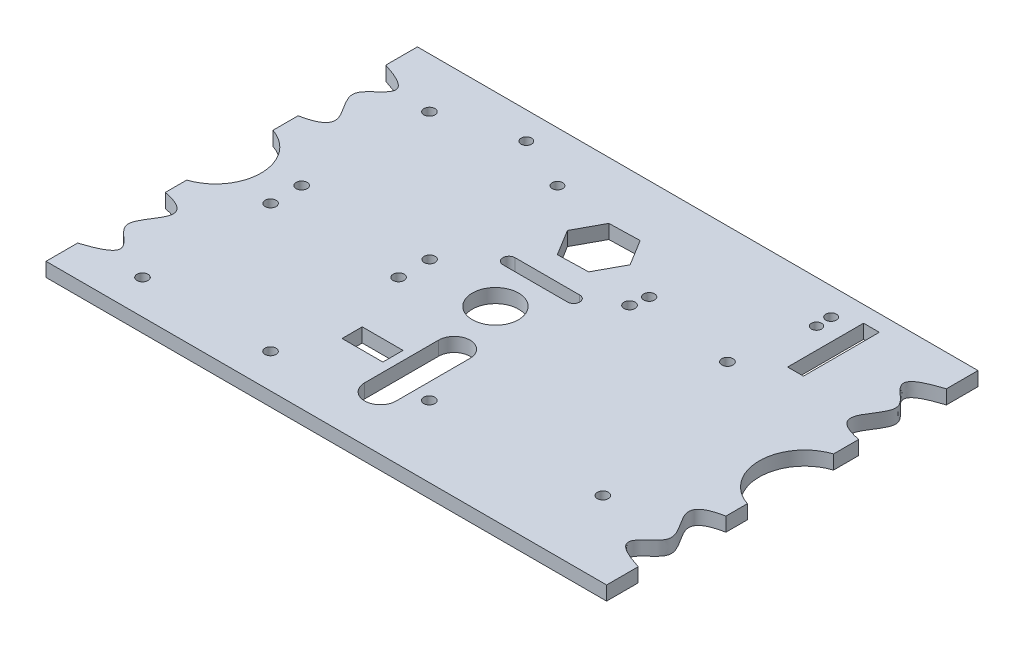
SolidWorks part; units mm, degrees
ref_plane "Front Plane" through (0, 0, 0) normal (0, 0, 1) x (1, 0, 0)
ref_plane "Top Plane" through (0, 0, 0) normal (0, 1, 0) x (1, 0, 0)
ref_plane "Right Plane" through (0, 0, 0) normal (1, 0, 0) x (0, 0, -1)
sketch "Sketch1" plane through (0, 0, 0) normal (0, 1, 0) x (1, 0, 0)
  line L0 (0, 0) -> (0, 70.7426) construction
  line L1 (80, 53) -> (-80, 53)
  line L2 (80, 53) -> (80, -53)
  line L3 (80, -53) -> (-80, -53)
  line L4 (-80, 53) -> (-80, -53)
  line L5 (0, 0) -> (109.5414, 0) construction
  line L6 (-80, -16.4693) -> (-80, -48.3678)
  line L10 (0, -37.5523) -> (0, -16.4693) construction
  line L11 (-4.4998, -37.5523) -> (-4.4998, -16.4693)
  line L12 (4.4998, -37.5523) -> (4.4998, -16.4693)
  line L13 (4.4998, 13.0904) -> (-13.9507, 13.0904) construction
  line L14 (-7.025, -24.0711) -> (-18.669, -24.0711)
  line L15 (-7.025, -24.0711) -> (-7.025, -29.8364)
  line L16 (-7.025, -29.8364) -> (-18.669, -29.8364)
  line L17 (-18.669, -24.0711) -> (-18.669, -29.8364)
  line L18 (4.4998, 11.3473) -> (-13.9507, 11.3473)
  line L19 (4.4998, 14.8334) -> (-13.9507, 14.8334)
  line L21 (-8.6559, 21.5986) -> (0.0582, 21.8306)
  line L22 (0.0582, 21.8306) -> (4.2143, 29.4932)
  line L23 (4.2143, 29.4932) -> (-0.3436, 36.9238)
  line L24 (-0.3436, 36.9238) -> (-9.0577, 36.6918)
  line L25 (-9.0577, 36.6918) -> (-13.2139, 29.0292)
  line L26 (-13.2139, 29.0292) -> (-8.6559, 21.5986)
  line L27 (51.9664, 48.3678) -> (56.4728, 48.3678)
  line L28 (51.9664, 48.3678) -> (51.9664, 26.6955)
  line L29 (51.9664, 26.6955) -> (56.4728, 26.6955)
  line L30 (56.4728, 48.3678) -> (56.4728, 26.6955)
  arc A0 (-80, -12.8265) -> (-80, 11.7732) centre (-84.0546, -0.5266) ccw
  circle A1 centre (-62.2504, 38.6873) radius 1.5728
  circle A2 centre (9.0805, -32.68) radius 1.5875
  circle A3 centre (57.3405, -31.41) radius 1.5875
  circle A4 centre (14.1605, 19.39) radius 1.5875
  circle A5 centre (42.1005, 19.39) radius 1.5875
  circle A6 centre (-25.7146, -6.6473) radius 1.5727
  circle A7 centre (-62.2504, -6.6473) radius 1.5727
  circle A8 centre (-62.2504, -43.2084) radius 1.5727
  circle A9 centre (-25.7146, -43.2084) radius 1.5727
  arc A10 (-4.4998, -37.5523) -> (4.4998, -37.5523) centre (0, -37.5523) ccw
  arc A11 (4.4998, -16.4693) -> (-4.4998, -16.4693) centre (0, -16.4693) ccw
  arc A12 (4.4998, 11.3473) -> (4.4998, 14.8334) centre (4.4998, 13.0904) ccw
  arc A13 (-13.9507, 14.8334) -> (-13.9507, 11.3473) centre (-13.9507, 13.0904) ccw
  circle A14 centre (-4.4998, 29.2612) radius 7.5493 construction
  circle A15 centre (-4.7255, 0) radius 6.5984
  circle A16 centre (-25.7146, 38.6873) radius 1.5
  circle A17 centre (-25.7146, 2.2101) radius 1.56
  circle A18 centre (-62.2504, 2.2101) radius 1.5735
  arc A19 (80, -12.8265) -> (80, 11.7732) centre (84.0546, -0.5266) cw
  circle A20 centre (14.8949, 24.261) radius 1.5376
  circle A21 centre (45.9834, 40.9244) radius 1.4553
  spline S0 degree 3 poles (-80, -43.9717) (-65.3857, -39.4048) (-89.0775, -33.6276) (-66.5269, -21.603) (-80, -18.9482) knots 0 0 0 0 0.464081 1 1 1 1
  spline S1 degree 3 poles (-80, 43.9717) (-65.3857, 39.4048) (-89.0775, 33.6276) (-66.5269, 21.603) (-80, 18.9482) knots 0 0 0 0 0.464081 1 1 1 1
  spline S2 degree 3 poles (80, 43.9717) (65.3857, 39.4048) (89.0775, 33.6276) (66.5269, 21.603) (80, 18.9482) knots 0 0 0 0 0.464081 1 1 1 1
  spline S3 degree 3 poles (80, -43.9717) (65.3857, -39.4048) (89.0775, -33.6276) (66.5269, -21.603) (80, -18.9482) knots 0 0 0 0 0.464081 1 1 1 1
  spline S6 degree 3 poles (47.3426, 45.238) (47.3426, 48.238) (44.3426, 48.238) (44.3426, 45.238) (44.3426, 42.238) (47.3426, 42.238) (47.3426, 45.238) (47.3426, 48.238) (44.3426, 48.238) knots -0.5 0 0 0 0.5 0.5 0.5 1 1 1 1.5 1.5 1.5 weights 1 0.333333 0.333333 1 0.333333 0.333333 1 0.333333 0.333333 only from (47.3426, 45.238) to (47.3426, 45.238) construction
  spline S7 degree 3 poles (-39.6524, 45.238) (-39.6524, 48.238) (-42.6524, 48.238) (-42.6524, 45.238) (-42.6524, 42.238) (-39.6524, 42.238) (-39.6524, 45.238) (-39.6524, 48.238) (-42.6524, 48.238) knots -0.5 0 0 0 0.5 0.5 0.5 1 1 1 1.5 1.5 1.5 weights 1 0.333333 0.333333 1 0.333333 0.333333 1 0.333333 0.333333 only from (-39.6524, 45.238) to (-39.6524, 45.238) construction
  spline S8 degree 3 poles (47.3426, 45.238) (47.3426, 48.238) (44.3426, 48.238) (44.3426, 45.238) (44.3426, 42.238) (47.3426, 42.238) (47.3426, 45.238) (47.3426, 48.238) (44.3426, 48.238) knots -0.5 0 0 0 0.5 0.5 0.5 1 1 1 1.5 1.5 1.5 weights 1 0.333333 0.333333 1 0.333333 0.333333 1 0.333333 0.333333 only from (47.3426, 45.238) to (47.3426, 45.238)
  spline S9 degree 3 poles (-39.6524, 45.238) (-39.6524, 48.238) (-42.6524, 48.238) (-42.6524, 45.238) (-42.6524, 42.238) (-39.6524, 42.238) (-39.6524, 45.238) (-39.6524, 48.238) (-42.6524, 48.238) knots -0.5 0 0 0 0.5 0.5 0.5 1 1 1 1.5 1.5 1.5 weights 1 0.333333 0.333333 1 0.333333 0.333333 1 0.333333 0.333333 only from (-39.6524, 45.238) to (-39.6524, 45.238)
  point P75 (0, -27.0108)
  point P86 (-4.7255, 13.0904)
  dimension "D1" = 160
  dimension "D2" = 106
extrude "Boss-Extrude1" add sketch "Sketch1" along normal blind 4
